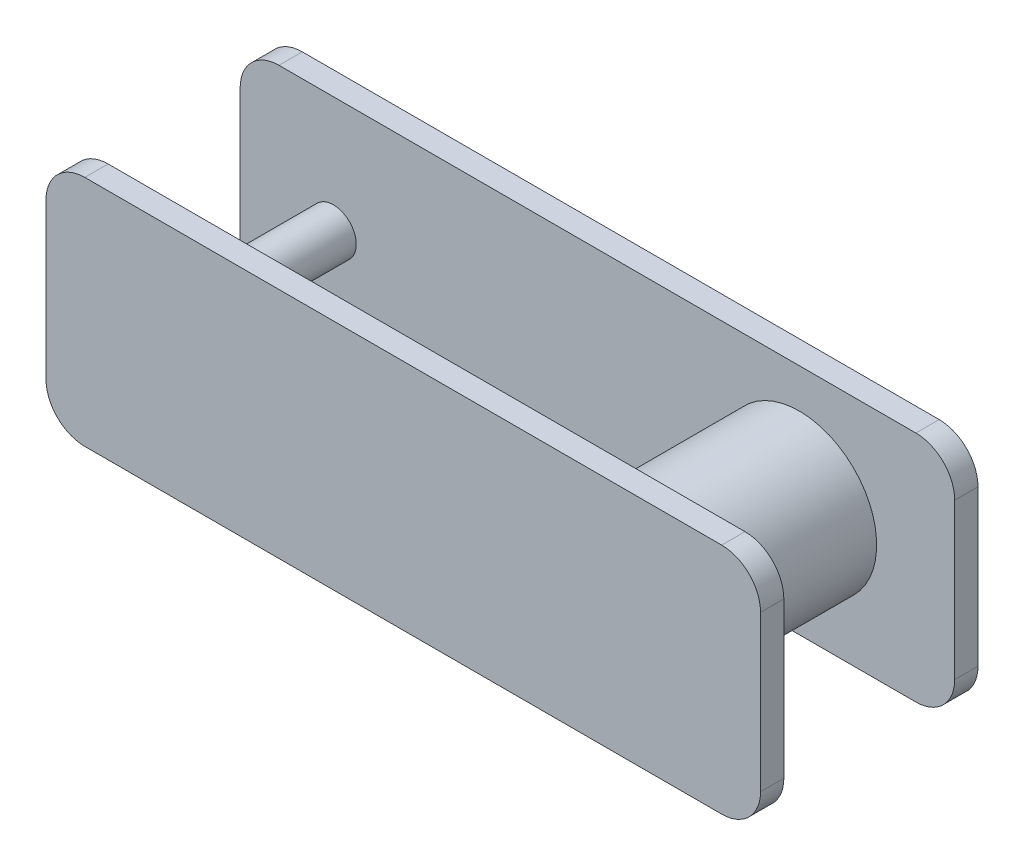
SolidWorks part; units mm, degrees
ref_plane "Front Plane" through (0, 0, 0) normal (0, 0, 1) x (1, 0, 0)
ref_plane "Top Plane" through (0, 0, 0) normal (0, 1, 0) x (1, 0, 0)
ref_plane "Right Plane" through (0, 0, 0) normal (1, 0, 0) x (0, 0, -1)
sketch "Sketch1" plane through (0, 0, 0) normal (0, 0, 1) x (1, 0, 0)
  line L1 (-7, 15) -> (75, 15)
  line L2 (-12, 10) -> (-12, -10)
  line L3 (-7, -15) -> (75, -15)
  line L4 (80, 10) -> (80, -10)
  arc A0 (75, 15) -> (80, 10) centre (75, 10) cw
  arc A1 (75, -15) -> (80, -10) centre (75, -10) ccw
  arc A2 (-12, -10) -> (-7, -15) centre (-7, -10) ccw
  arc A3 (-7, 15) -> (-12, 10) centre (-7, 10) ccw
  dimension "D5" = 5
  dimension "D1" = 15
  dimension "D2" = 15
  dimension "D3" = 12
  dimension "D4" = 80
extrude "Boss-Extrude1" add sketch "Sketch1" along normal blind 3
sketch "Sketch2" plane through (0, 0, 3) normal (0, 0, 1) x (1, 0, 0)
  line L0 (0, 0) -> (60, 0) construction
  circle A0 centre (0, 0) radius 2.95
  circle A1 centre (60, 0) radius 9.95
  dimension "D1" = 5.9
  dimension "D3" = 19.9
  dimension "D2" = 60
extrude "Boss-Extrude2" add sketch "Sketch2" along normal blind 22
sketch "Sketch3" plane through (0, 0, 25) normal (0, 0, 1) x (1, 0, 0)
  line L4 (75, 15) -> (-7, 15)
  line L5 (-12, 10) -> (-12, -10)
  line L6 (-7, -15) -> (75, -15)
  line L7 (80, -10) -> (80, 10)
  line L8 (75, 15) -> (-7, 15)
  line L9 (-12, 10) -> (-12, -10)
  line L10 (-7, -15) -> (75, -15)
  line L11 (80, -10) -> (80, 10)
  arc A4 (80, 10) -> (75, 15) centre (75, 10) ccw
  arc A5 (-7, 15) -> (-12, 10) centre (-7, 10) ccw
  arc A6 (-12, -10) -> (-7, -15) centre (-7, -10) ccw
  arc A7 (75, -15) -> (80, -10) centre (75, -10) ccw
  arc A8 (80, 10) -> (75, 15) centre (75, 10) ccw
  arc A9 (-7, 15) -> (-12, 10) centre (-7, 10) ccw
  arc A10 (-12, -10) -> (-7, -15) centre (-7, -10) ccw
  arc A11 (75, -15) -> (80, -10) centre (75, -10) ccw
  dimension "D1" = 0
extrude "Boss-Extrude3" add sketch "Sketch3" along normal blind 3
ref_plane "Plane1" through (0, 0, 4) normal (0, 0, 1) x (1, 0, 0)
